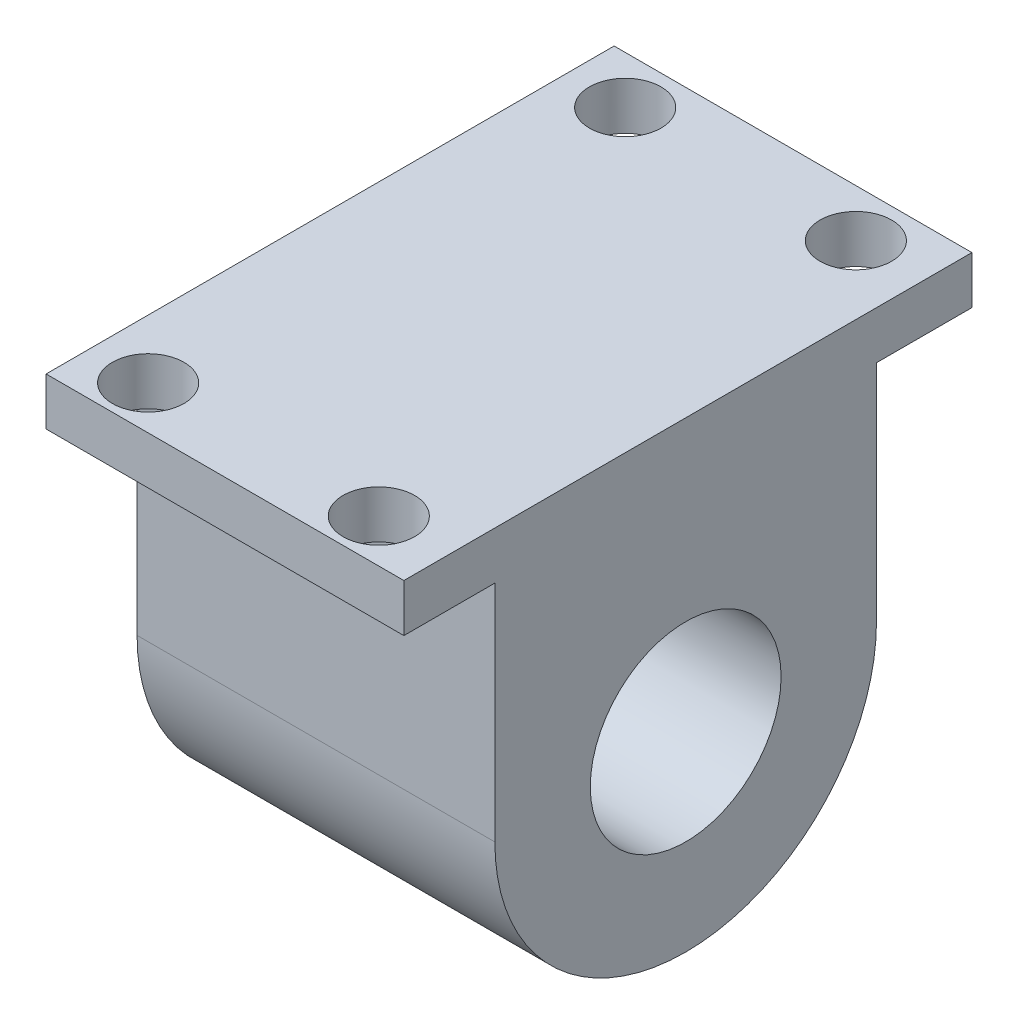
SolidWorks part; units mm, degrees
ref_plane "Front Plane" through (0, 0, 0) normal (0, 0, 1) x (1, 0, 0)
ref_plane "Top Plane" through (0, 0, 0) normal (0, 1, 0) x (1, 0, 0)
ref_plane "Right Plane" through (0, 0, 0) normal (1, 0, 0) x (0, 0, -1)
sketch "Sketch2" plane through (0, 0, 0) normal (1, 0, 0) x (0, 0, -1)
  line L0 (-7.815, 11.4) -> (-11.815, 11.4)
  line L1 (-4, 0) -> (4, 0)
  line L2 (-8, 0) -> (-8, 9.4)
  line L3 (-7.815, 11.4) -> (8, 11.4)
  line L4 (8, 0) -> (8, 9.4)
  line L6 (-11.815, 11.4) -> (-11.815, 9.4)
  line L7 (-11.815, 9.4) -> (-8, 9.4)
  line L8 (12, 11.4) -> (12, 9.4)
  line L11 (-11.815, 11.4) -> (12, 11.4)
  line L12 (8, 9.4) -> (12, 9.4)
  circle A0 centre (0, 0) radius 4
  arc A1 (-8, 0) -> (8, 0) centre (0, 0) ccw
  point P8 (0.0925, 11.4)
  dimension "D1" = 8
  dimension "D2" = 16
  dimension "D3" = 11.4
  dimension "D4" = 4
  dimension "D5" = 4
extrude "Boss-Extrude1" add sketch "Sketch2" along normal blind 15 contours L2 A1 L4 L12 L8 L11 L3 L0 L6 L7 A0
sketch "Sketch3" plane through (0, 9.4, 0) normal (0, -1, 0) x (1, 0, 0)
  line L0 (0, -8) -> (0, -12) construction
  circle A0 centre (2.4644, -10) radius 1.5
  circle A1 centre (12.1341, -10) radius 1.5
  dimension "D1" = 3
  dimension "D2" = 3
  dimension "D3" = 2.4644
extrude "Cut-Extrude1" cut sketch "Sketch3" against normal blind 15
mirror "Mirror1" about plane through (0, 0, 0) normal (0, 0, 1) of "Cut-Extrude1"
